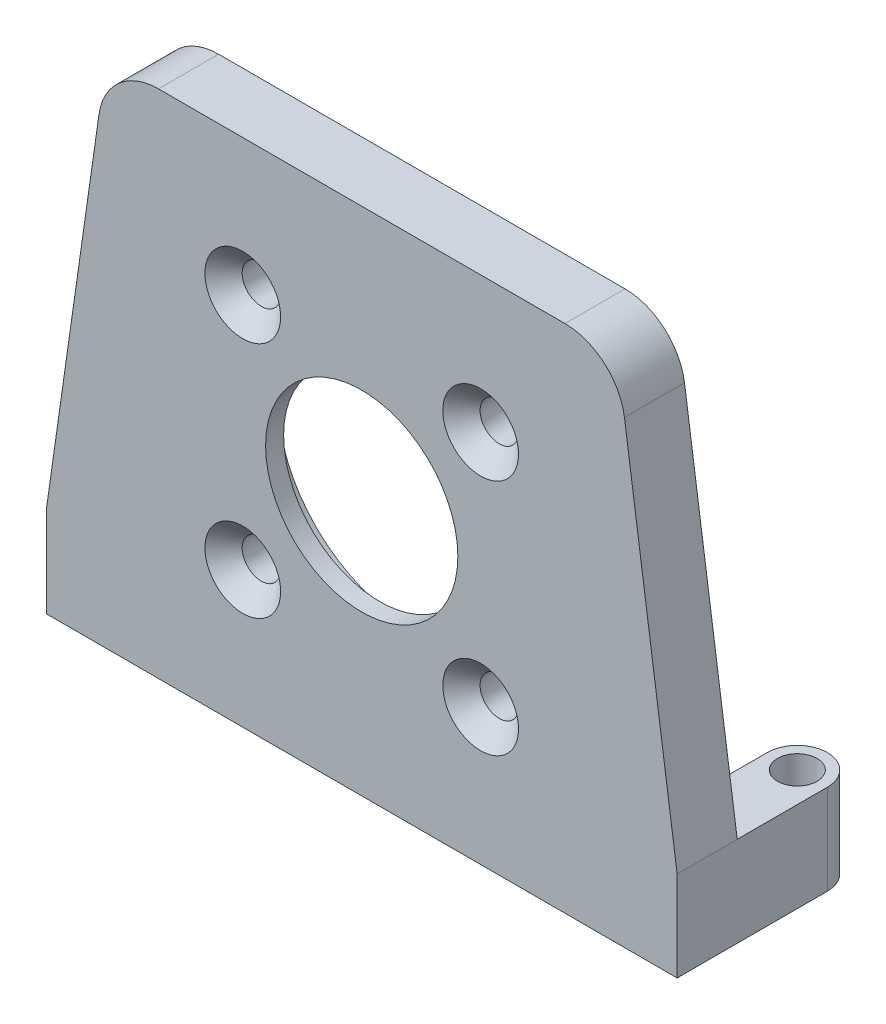
SolidWorks part; units mm, degrees
ref_plane "Ebene vorne" through (0, 0, 0) normal (0, 0, 1) x (1, 0, 0)
ref_plane "Ebene oben" through (0, 0, 0) normal (0, 1, 0) x (1, 0, 0)
ref_plane "Ebene rechts" through (0, 0, 0) normal (1, 0, 0) x (0, 0, -1)
sketch "Skizze1" plane through (0, 0, 0) normal (0, 0, 1) x (1, 0, 0)
  line L0 (26.25, 21.25) -> (1.9643, 21.25) construction
  line L1 (0, 0) -> (52.5, 0)
  line L2 (0, 0) -> (0, 7.5)
  line L3 (9.3365, 42.5) -> (43.1635, 42.5)
  line L4 (52.5, 0) -> (52.5, 7.5)
  line L5 (26.25, 21.25) -> (50.5357, 21.25) construction
  line L6 (0, 7.5) -> (4.3867, 38.2071)
  line L7 (52.5, 7.5) -> (48.1133, 38.2071)
  circle A0 centre (26.25, 21.25) radius 8
  arc A1 (48.1133, 38.2071) -> (43.1635, 42.5) centre (43.1635, 37.5) ccw
  arc A2 (4.3867, 38.2071) -> (9.3365, 42.5) centre (9.3365, 37.5) cw
  point P9 (47.5, 42.5)
  point P11 (0, 42.5)
  point P17 (5, 42.5)
  point P20 (52.5, 7.5)
  point P23 (0, 7.5)
  dimension "D2" = 16
  dimension "D6" = 5
  dimension "D8" = 5
  dimension "D1" = 52.5
  dimension "D3" = 42.5
  dimension "D4" = 5
  dimension "D5" = 21.25
  dimension "D7" = 7.5
extrude "Aufsatz-Linear austragen1" add sketch "Skizze1" along normal blind 5
sketch "Skizze4" plane through (0, 0, 0) normal (0, -1, 0) x (1, 0, 0)
  line L1 (52.5, 0) -> (47.5, 0)
  line L2 (52.5, 0) -> (52.5, -7.5)
  line L4 (47.5, 0) -> (47.5, -7.5)
  line L7 (0, 0) -> (5, 0)
  line L8 (0, 0) -> (0, -7.5)
  line L10 (5, 0) -> (5, -7.5)
  arc A0 (47.5, -7.5) -> (52.5, -7.5) centre (50, -7.5) ccw
  arc A1 (0, -7.5) -> (5, -7.5) centre (2.5, -7.5) ccw
  dimension "D1" = 2.5
  dimension "D2" = 7.5
extrude "Aufsatz-Linear austragen2" add sketch "Skizze4" against normal blind 7.5
hole_wizard "Formsenkung für M3 Senkschraube mit Schlitz/Kreuzschlitz1" positions "Skizze11" profile "Skizze10" countersink size "M3" standard "DIN" end condition through all
sketch "Skizze11" plane through (0, 0, 5) normal (0, 0, 1) x (1, 0, 0)
  line L1 (16.3505, 31.1495) -> (36.1495, 31.1495) construction
  line L2 (16.3505, 31.1495) -> (16.3505, 11.3505) construction
  line L3 (16.3505, 11.3505) -> (36.1495, 11.3505) construction
  line L4 (36.1495, 31.1495) -> (36.1495, 11.3505) construction
  circle A0 centre (26.25, 21.25) radius 14 construction
  point P5 (16.3505, 31.1495)
  point P6 (36.1495, 11.3505)
  point P9 (16.3505, 11.3505)
  point P10 (36.1495, 31.1495)
  dimension "D1" = 28
sketch "Skizze10" plane through (16.3505, 31.1495, 5) normal (1, 0, 0) x (0, -1, 0)
  line L0 (0, 0) -> (0, 15)
  line L1 (0, 15) -> (1.6, 15)
  line L2 (1.6, 15) -> (1.6, 1.55)
  line L3 (1.6, 1.55) -> (3.15, 0)
  line L5 (3.15, 0) -> (0, 0)
  line L6 (-1.6, 1.55) -> (-3.15, 0) construction
  line L11 (0, -6.35) -> (0, 107.95) construction
  dimension "Bohrerdurchmesser" = 3.2
  dimension "Bohrungstiefe" = 15
  dimension "Senkdurchmesser (Oben)" = 6.3
  dimension "Senkwinkel (Oben)" = 90
hole_wizard "M4 Gewindebohrung2" positions "Skizze13" profile "Skizze14" tap size "M4" standard "DIN"
sketch "Skizze13" plane through (0, 0, 0) normal (0, -1, 0) x (-1, 0, 0)
  line L0 (0, -5) -> (-52.5, -5) construction
  point P2 (-2.5, 7.5)
  point P7 (-50, 7.5)
  point P11 (-50, -2.5)
  point P13 (-2.5, -2.5)
  dimension "D1" = 2.5
cosmetic thread "Bohrungsgewinde3" parameters "D1"=7.5, "D2"=4
cosmetic thread "Bohrungsgewinde4" parameters "D1"=7.5, "D2"=4
sketch "Skizze14" plane through (2.5, 0, -7.5) normal (1, 0, 0) x (0, 0, -1)
  line L0 (0, 0) -> (0, 13.9914)
  line L1 (0, 13.9914) -> (1.65, 13)
  line L2 (1.65, 13) -> (1.65, 0)
  line L5 (1.65, 0) -> (0, 0)
  line L10 (0, 13.9914) -> (-1.65, 13) construction
  line L11 (0, -6.35) -> (0, 107.95) construction
  dimension "Bohrerdurchmesser" = 3.3
  dimension "Bohrungstiefe" = 13
  dimension "Spitzenwinkel" = 118
cosmetic thread "Bohrungsgewinde5" parameters "D1"=10, "D2"=4
cosmetic thread "Bohrungsgewinde6" parameters "D1"=10, "D2"=4
sketch "Skizze15" plane through (0, 0, 0) normal (0, 0, -1) x (-1, 0, 0)
  circle A0 centre (-26.25, 21.25) radius 18.25
  dimension "D1" = 36.5
extrude "Schnitt-Linear austragen1" cut sketch "Skizze15" against normal blind 1
sketch "Skizze16" plane through (0, 0, 1) normal (0, 0, -1) x (-1, 0, 0)
  circle A0 centre (-26.25, 21.25) radius 11.0125
  dimension "D1" = 22.025
extrude "Schnitt-Linear austragen2" cut sketch "Skizze16" against normal blind 2.5
